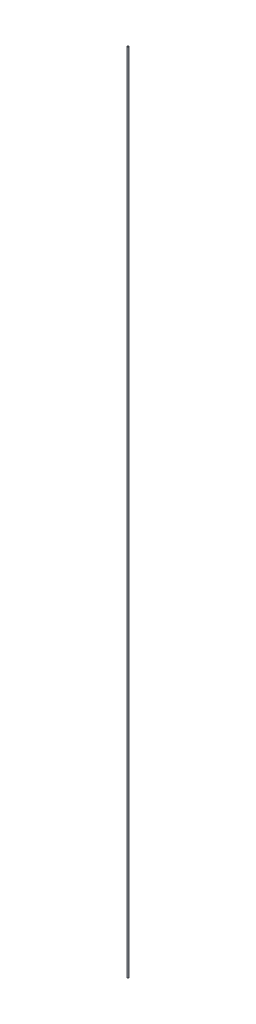
SolidWorks part; units mm, degrees
ref_plane "Front Plane" through (0, 0, 0) normal (0, 0, 1) x (1, 0, 0)
ref_plane "Top Plane" through (0, 0, 0) normal (0, 1, 0) x (1, 0, 0)
ref_plane "Right Plane" through (0, 0, 0) normal (1, 0, 0) x (0, 0, -1)
sketch "Sketch1" plane through (0, 0, 0) normal (0, 0, 1) x (1, 0, 0)
  line L0 (0, 0) -> (0, 7872.984)
  dimension "Length from Tank Model" = 7872.984
sweep "Sweep1" add path "Sketch1" circular profile diameter 12.7 parameters "D3"=12.7
equation "\"rebar diameter\"= .5"
equation "\"D3@Sweep1\"=\"rebar diameter\""
